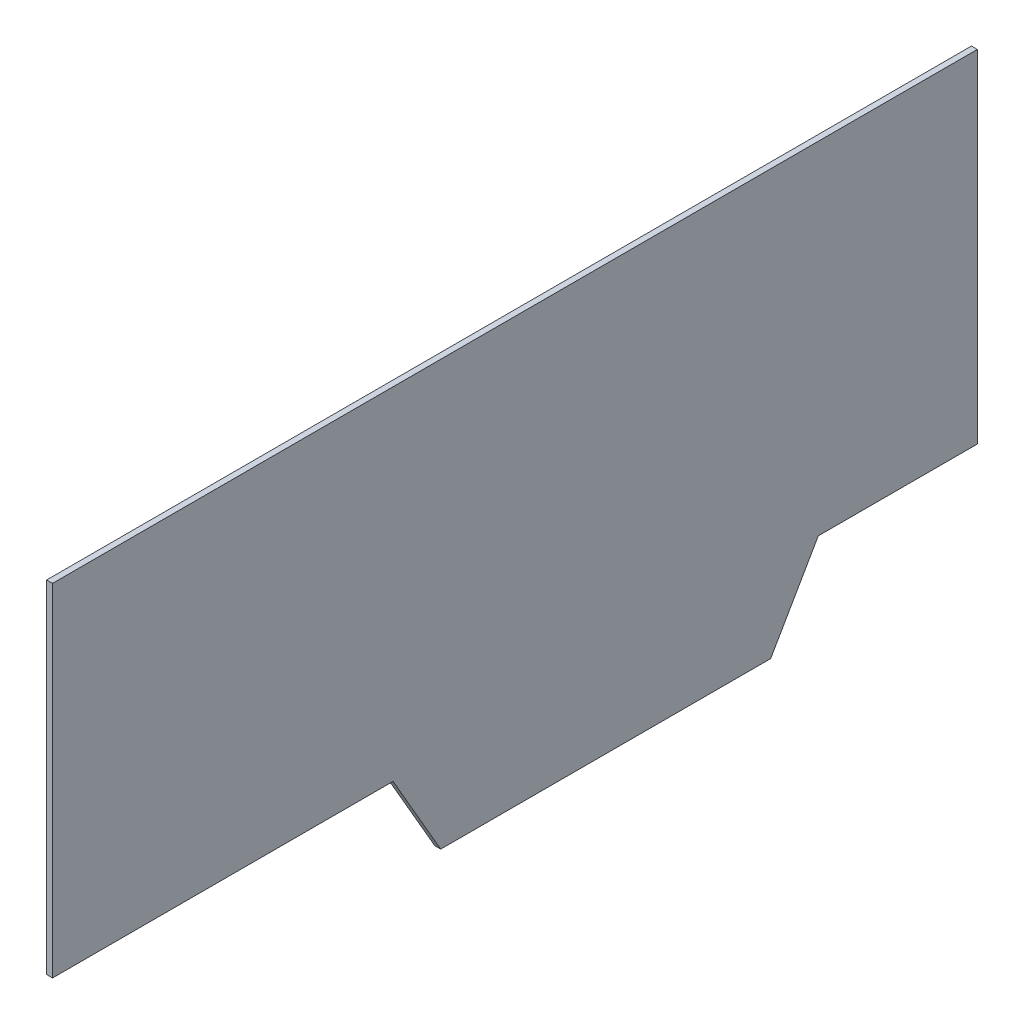
SolidWorks part; units mm, degrees
material "6061-T6 (SS)"
ref_plane "X-Y Datum" through (0, 0, 0) normal (0, 0, 1) x (1, 0, 0)
ref_plane "X-Z Datum" through (0, 0, 0) normal (0, 1, 0) x (1, 0, 0)
ref_plane "Y-Z Datum" through (0, 0, 0) normal (1, 0, 0) x (0, 0, -1)
sketch "Sketch1" plane through (0, 0, 0) normal (1, 0, 0) x (0, 0, -1)
  line L1 (-249.174, 88.9) -> (249.174, 88.9)
  line L2 (-249.174, 88.9) -> (-249.174, -88.9)
  line L3 (-249.174, -88.9) -> (249.174, -88.9)
  line L4 (249.174, 88.9) -> (249.174, -88.9)
  line L5 (-249.174, 88.9) -> (249.174, -88.9) construction
  line L6 (-249.174, -88.9) -> (249.174, 88.9) construction
  point P0 (0, 0)
  dimension "D1" = 177.8
  dimension "D2" = 498.348
extrude "Boss-Extrude1" add sketch "Sketch1" along normal mid plane 3.175
sketch "Sketch2" plane through (1.5875, 0, 0) normal (1, 0, 0) x (0, 0, -1)
  line L0 (249.174, -88.9) -> (249.174, -95.25)
  line L1 (249.174, -95.25) -> (163.449, -95.25)
  line L2 (163.449, -95.25) -> (137.7858, -139.7)
  line L3 (137.7858, -139.7) -> (-40.0142, -139.7)
  line L5 (-249.174, -88.9) -> (249.174, -88.9) construction
  line L6 (-249.174, -88.9) -> (249.174, -88.9)
  line L7 (-249.174, -88.9) -> (-249.174, -95.25)
  line L8 (-249.174, -95.25) -> (-65.6774, -95.25)
  line L9 (-65.6774, -95.25) -> (-40.0142, -139.7)
  line L10 (249.174, -88.9) -> (249.174, 88.9) construction
  line L11 (-249.174, -88.9) -> (249.174, -88.9) construction
  point P5 (0, 0)
  point P13 (0, 0)
  point P16 (-21.2394, -177.8)
  point P19 (-246.568, -88.9)
  dimension "D1" = 6.35
  dimension "D2" = 85.725
  dimension "D3" = 177.8
  dimension "D4" = 120
  dimension "D5" = 6.35
  dimension "D6" = 120
  dimension "D7" = 50.8
extrude "Boss-Extrude2" add sketch "Sketch2" against normal blind 3.175
